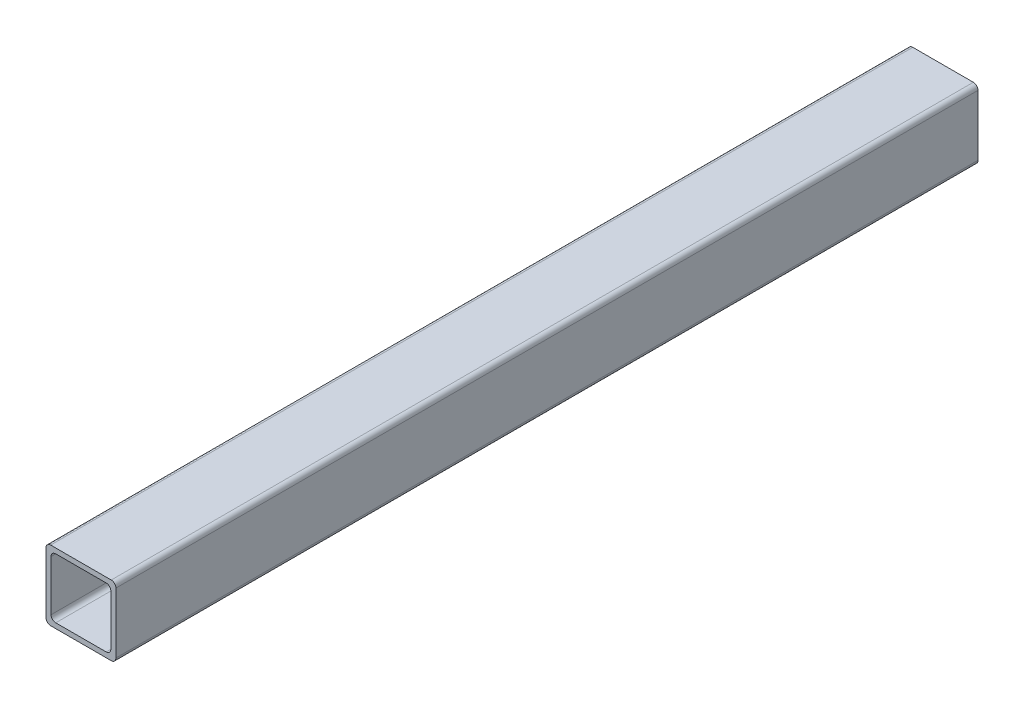
SolidWorks part; units mm, degrees
material "ASTM A500 Grade B Steel"
ref_plane "Front Plane" through (0, 0, 0) normal (0, 0, 1) x (1, 0, 0)
ref_plane "Top Plane" through (0, 0, 0) normal (0, 1, 0) x (1, 0, 0)
ref_plane "Right Plane" through (0, 0, 0) normal (1, 0, 0) x (0, 0, -1)
sketch "Sketch1" plane through (0, 0, 0) normal (0, 0, 1) x (1, 0, 0)
  line L0 (5.3086, -2.7686) -> (32.7914, -2.7686)
  line L1 (2.54, 0) -> (35.56, 0)
  line L2 (0, -2.54) -> (0, -35.56)
  line L3 (2.54, -38.1) -> (35.56, -38.1)
  line L4 (38.1, -2.54) -> (38.1, -35.56)
  line L5 (35.3314, -5.3086) -> (35.3314, -32.7914)
  line L6 (5.3086, -35.3314) -> (32.7914, -35.3314)
  line L7 (2.7686, -5.3086) -> (2.7686, -32.7914)
  line L8 (0, 0) -> (0, -38.1) construction
  line L9 (0, -38.1) -> (38.1, -38.1) construction
  line L10 (38.1, 0) -> (38.1, -38.1) construction
  line L11 (2.7686, -2.7686) -> (2.7686, -35.3314) construction
  line L12 (2.7686, -35.3314) -> (35.3314, -35.3314) construction
  line L13 (35.3314, -2.7686) -> (35.3314, -35.3314) construction
  line L14 (2.7686, -2.7686) -> (35.3314, -2.7686) construction
  line L15 (0, 0) -> (38.1, 0) construction
  arc A0 (0, -35.56) -> (2.54, -38.1) centre (2.54, -35.56) ccw
  arc A1 (38.1, -35.56) -> (35.56, -38.1) centre (35.56, -35.56) cw
  arc A2 (2.7686, -32.7914) -> (5.3086, -35.3314) centre (5.3086, -32.7914) ccw
  arc A3 (32.7914, -35.3314) -> (35.3314, -32.7914) centre (32.7914, -32.7914) ccw
  arc A4 (35.3314, -5.3086) -> (32.7914, -2.7686) centre (32.7914, -5.3086) ccw
  arc A5 (38.1, -2.54) -> (35.56, 0) centre (35.56, -2.54) ccw
  arc A6 (0, -2.54) -> (2.54, 0) centre (2.54, -2.54) cw
  arc A7 (5.3086, -2.7686) -> (2.7686, -5.3086) centre (5.3086, -5.3086) ccw
  point P12 (0, -38.1)
  dimension "D4" = 2.54
  dimension "D3" = 2.7686
extrude "Boss-Extrude1" add sketch "Sketch1" along normal blind 470
